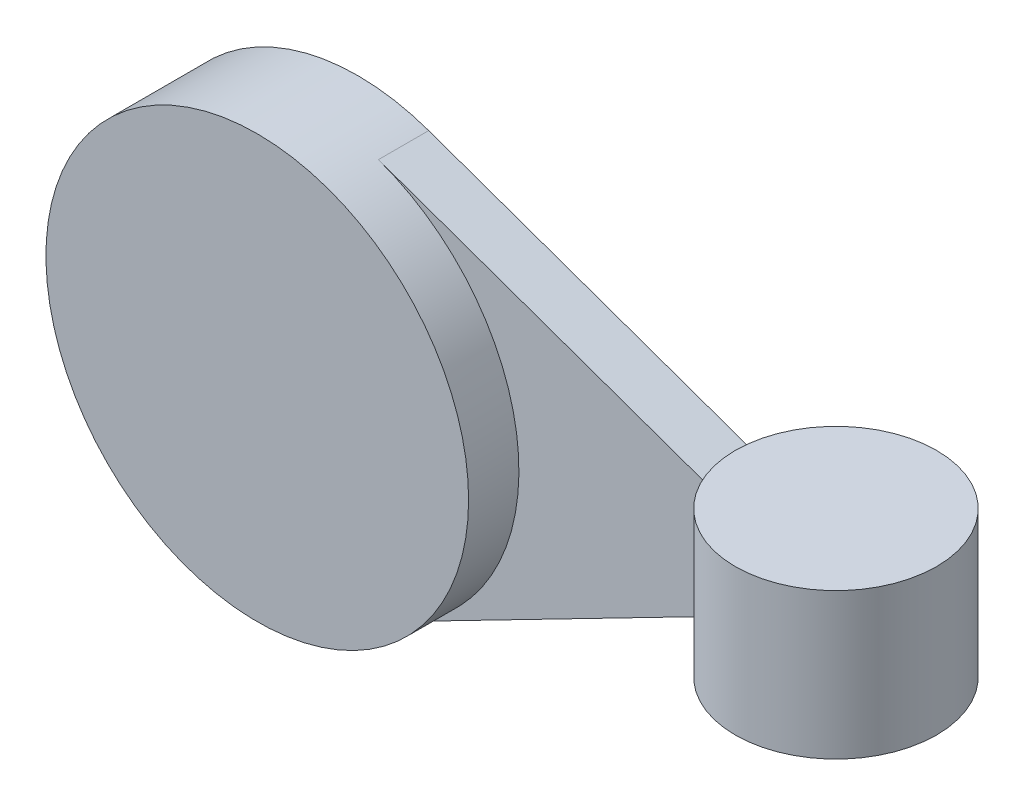
SolidWorks part; units mm, degrees
material "A286 铁基超合金"
ref_plane "前视基准面" through (0, 0, 0) normal (0, 0, 1) x (1, 0, 0)
ref_plane "上视基准面" through (0, 0, 0) normal (0, 1, 0) x (1, 0, 0)
ref_plane "右视基准面" through (0, 0, 0) normal (1, 0, 0) x (0, 0, -1)
other "Configuration Table"
sketch "草图1" plane through (0, 0, 0) normal (0, 0, 1) x (1, 0, 0)
  circle A0 centre (0, 0) radius 42
  dimension "D1" = 84
extrude "凸台-拉伸1" add sketch "草图1" along normal blind 20
sketch "草图2" plane through (0, 0, 20) normal (0, 0, 1) x (1, 0, 0)
  line L0 (0, 0) -> (150.9371, 0) construction
  line L1 (100, 22.7173) -> (100, -21.6499) construction
  line L2 (100, 20) -> (100, 15)
  line L3 (80, 20) -> (100, 20)
  line L4 (80, 20) -> (80, -9)
  line L8 (80, -9) -> (88, -9)
  arc A1 (100, 15) -> (88, -9) centre (100, 0) ccw
  dimension "D2" = 30
  dimension "D1" = 100
  dimension "D3" = 20
  dimension "D4" = 20
  dimension "D5" = 9
revolve "旋转1" add sketch "草图2" angle 360 about L1
sketch "草图3" plane through (0, 0, 20) normal (0, 0, 1) x (1, 0, 0)
  line L0 (14.0695, 39.5734) -> (86, 14)
  line L1 (19.2087, -37.35) -> (86, -3)
  line L4 (86, 14) -> (86, -3)
  circle A1 centre (0, 0) radius 42
  arc A2 (14.0695, 39.5734) -> (19.2087, -37.35) centre (0, 0) ccw
  dimension "D2" = 86
  dimension "D3" = 14
  dimension "D4" = 3
  dimension "D1" = 0
extrude "凸台-拉伸2" add sketch "草图3" along normal mid plane 10
sketch "草图4" plane through (0, 0, 0) normal (0, 0, -1) x (-1, 0, 0)
  circle A1 centre (0, 0) radius 42
  circle A2 centre (0, 0) radius 42
  dimension "D1" = 0
extrude "切除-拉伸1" cut sketch "草图4" against normal up to surface (15 mm away) up to face at (54.954, 3.5149, 15)
sketch "草图5" plane through (0, 0, 25) normal (0, 0, 1) x (1, 0, 0)
  line L3 (80.6351, -5.7591) -> (80.6351, 15.9074)
  line L4 (80.6351, 15.9074) -> (14.0695, 39.5734)
  line L5 (19.2087, -37.35) -> (80.6351, -5.7591)
  arc A1 (14.0695, 39.5734) -> (19.2087, -37.35) centre (0, 0) ccw
  arc A2 (14.0695, 39.5734) -> (19.2087, -37.35) centre (0, 0) ccw construction
  circle A3 centre (0, 0) radius 42
  dimension "D1" = 0
extrude "凸台-拉伸3" add sketch "草图5" along normal blind 10
